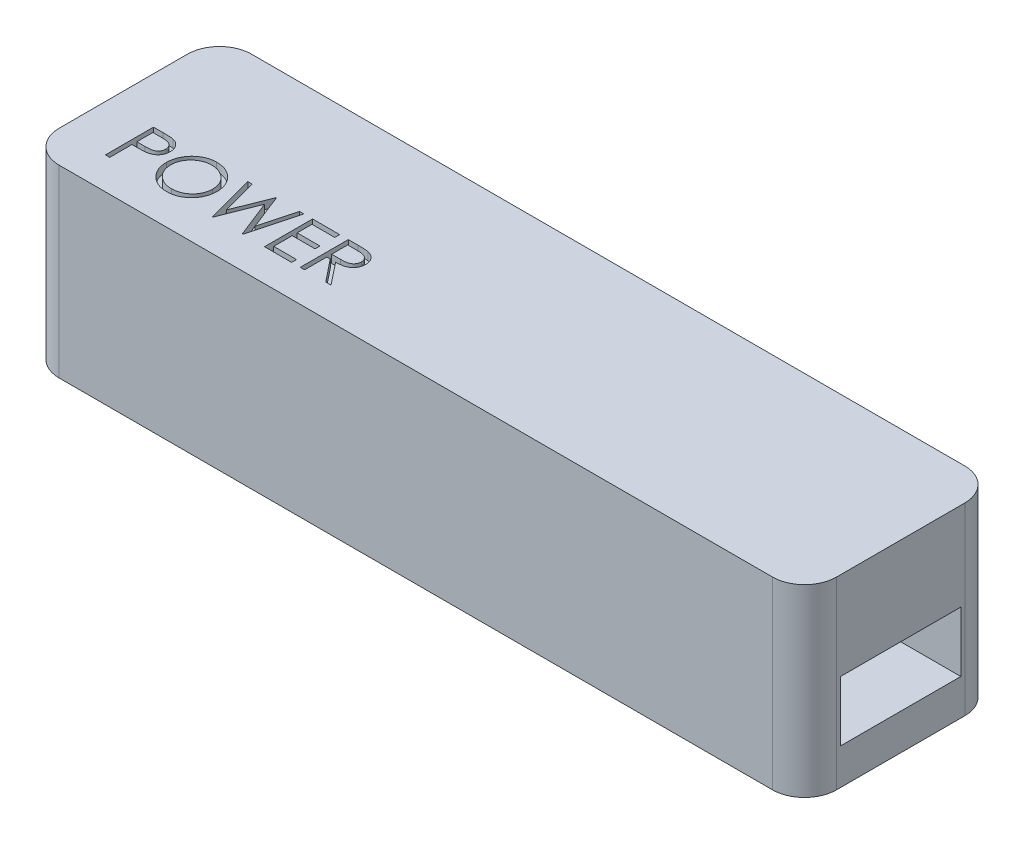
SolidWorks part; units mm, degrees
ref_plane "Front Plane" through (0, 0, 0) normal (0, 0, 1) x (1, 0, 0)
ref_plane "Top Plane" through (0, 0, 0) normal (0, 1, 0) x (1, 0, 0)
ref_plane "Right Plane" through (0, 0, 0) normal (1, 0, 0) x (0, 0, -1)
sketch "Sketch1" plane through (0, 0, 0) normal (0, 1, 0) x (1, 0, 0)
  line L1 (44.5, -12) -> (-44.5, -12)
  line L2 (48.5, -8) -> (48.5, 8)
  line L3 (44.5, 12) -> (-44.5, 12)
  line L4 (-48.5, -8) -> (-48.5, 8)
  line L5 (48.5, -12) -> (-48.5, 12) construction
  line L6 (48.5, 12) -> (-48.5, -12) construction
  arc A0 (48.5, 8) -> (44.5, 12) centre (44.5, 8) ccw
  arc A1 (44.5, -12) -> (48.5, -8) centre (44.5, -8) ccw
  arc A2 (-44.5, -12) -> (-48.5, -8) centre (-44.5, -8) cw
  arc A3 (-44.5, 12) -> (-48.5, 8) centre (-44.5, 8) ccw
  point P0 (0, 0)
  dimension "D3" = 4
  dimension "D1" = 24
  dimension "D2" = 97
extrude "Boss-Extrude1" add sketch "Sketch1" along normal blind 23
sketch "Sketch2" plane through (48.5, 0, 0) normal (1, 0, 0) x (0, 0, -1)
  line L0 (-8, 0) -> (8, 0) construction
  line L1 (7.5, 4.5) -> (-7.5, 4.5)
  line L2 (7.5, 4.5) -> (7.5, 12)
  line L3 (7.5, 12) -> (-7.5, 12)
  line L4 (-7.5, 4.5) -> (-7.5, 12)
  line L5 (7.5, 4.5) -> (-7.5, 12) construction
  line L6 (7.5, 12) -> (-7.5, 4.5) construction
  point P0 (0, 8.25)
  point P5 (0, 0)
  dimension "D1" = 15
  dimension "D2" = 7.5
  dimension "D3" = 4.5
extrude "Cut-Extrude1" cut sketch "Sketch2" against normal blind 10
sketch "Sketch3" plane through (0, 23, 0) normal (0, 1, 0) x (1, 0, 0)
  line L0 (-44.5, -12) -> (44.5, -12) construction
  line L1 (-48.5, 8) -> (-48.5, -8) construction
  text T0 "POWER" font "Century Gothic" height 6
  dimension "D1" = 4
  dimension "D2" = 5
extrude "Cut-Extrude2" cut sketch "Sketch3" against normal blind 1
